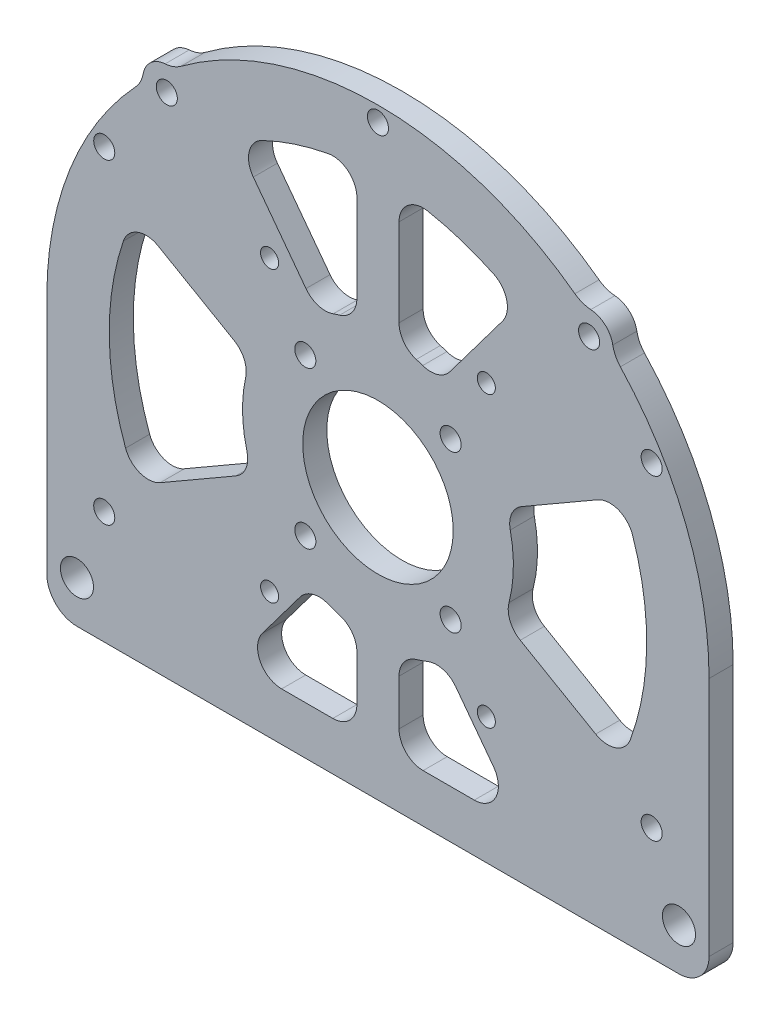
SolidWorks part; units mm, degrees
ref_plane "前视基准面" through (0, 0, 0) normal (0, 0, 1) x (1, 0, 0)
ref_plane "上视基准面" through (0, 0, 0) normal (0, 1, 0) x (1, 0, 0)
ref_plane "右视基准面" through (0, 0, 0) normal (1, 0, 0) x (0, 0, -1)
other "Configuration Table"
sketch "草图2" plane through (0, 0, 0) normal (0, 0, 1) x (1, 0, 0)
  line L0 (40.8909, 11.2177) -> (40.8909, 84.7823) construction
  line L1 (36.7823, 88.8909) -> (-36.7823, 88.8909) construction
  line L2 (-40.8909, 84.7823) -> (-40.8909, 11.2177) construction
  line L3 (40.8909, 11.2177) -> (40.8909, 84.7823)
  line L4 (36.7823, 88.8909) -> (-36.7823, 88.8909)
  line L5 (-40.8909, 84.7823) -> (-40.8909, 11.2177)
  line L6 (-55, 48) -> (-55, 3)
  line L7 (-55, 98) -> (-55, -2) construction
  line L8 (-55, 3) -> (55, 3)
  line L9 (55, 98) -> (55, -2) construction
  line L10 (55, 3) -> (55, 48.115)
  line L11 (-23.2721, 3) -> (23.2721, 3) construction
  circle A0 centre (35.074, 87.25) radius 1.55 construction
  circle A1 centre (-35.074, 87.25) radius 1.55 construction
  circle A2 centre (-50, 10) radius 2.55 construction
  circle A3 centre (50, 10) radius 2.55 construction
  circle A4 centre (-18, 24) radius 1.25 construction
  circle A5 centre (18, 24) radius 1.25 construction
  circle A6 centre (12.07, 35) radius 1.75 construction
  circle A7 centre (-12.07, 35) radius 1.75 construction
  circle A8 centre (-18, 72) radius 1.25 construction
  circle A9 centre (-12.07, 61) radius 1.75 construction
  circle A10 centre (18, 72) radius 1.25 construction
  circle A11 centre (12.07, 61) radius 1.75 construction
  circle A12 centre (35.074, 87.25) radius 1.55
  circle A13 centre (-35.074, 87.25) radius 1.55
  circle A14 centre (-50, 10) radius 2.55
  circle A15 centre (50, 10) radius 2.55
  circle A16 centre (-18, 24) radius 1.25
  circle A17 centre (18, 24) radius 1.25
  circle A18 centre (12.07, 35) radius 1.75
  circle A19 centre (-12.07, 35) radius 1.75
  circle A20 centre (-18, 72) radius 1.25
  circle A21 centre (-12.07, 61) radius 1.75
  circle A22 centre (18, 72) radius 1.25
  circle A23 centre (12.07, 61) radius 1.75
  circle A24 centre (0, 48) radius 12.5 construction
  circle A25 centre (0, 48) radius 12.5
  arc A26 (31.6228, 3) -> (-31.6228, 3) centre (0, 48) ccw
  arc A27 (40.8909, 11.2177) -> (40.8909, 84.7823) centre (0, 48) ccw construction
  circle A28 centre (45.4663, 21.75) radius 1.5
  circle A29 centre (45.4663, 21.75) radius 1.5
  circle A30 centre (45.4663, 74.25) radius 1.5
  circle A31 centre (45.4663, 74.25) radius 1.5
  circle A32 centre (0, 100.5) radius 1.5
  circle A33 centre (0, 100.5) radius 1.5
  circle A34 centre (-45.4663, 21.75) radius 1.5
  circle A35 centre (-45.4663, 21.75) radius 1.5
  circle A36 centre (-45.4663, 74.25) radius 1.5
  circle A37 centre (-45.4663, 74.25) radius 1.5
  arc A38 (36.7823, 88.8909) -> (-36.7823, 88.8909) centre (0, 48) ccw construction
  arc A39 (-40.8909, 84.7823) -> (-40.8909, 11.2177) centre (0, 48) ccw construction
  arc A40 (40.8909, 11.2177) -> (40.8909, 84.7823) centre (0, 48) ccw
  arc A41 (36.7823, 88.8909) -> (-36.7823, 88.8909) centre (0, 48) ccw
  arc A42 (-40.8909, 84.7823) -> (-40.8909, 11.2177) centre (0, 48) ccw
  circle A48 centre (-35.074, 87.25) radius 4
  circle A49 centre (35.074, 87.25) radius 4
  dimension "D1" = 110
  dimension "D8" = 8
  dimension "D9" = 8
  dimension "D7" = 0
  dimension "D2" = 0
  dimension "D3" = 0
  dimension "D4" = 0
  dimension "D5" = 0
  dimension "D6" = 0
extrude "凸台-拉伸1" add sketch "草图2" along normal blind 4
sketch "草图3" plane through (0, 0, 4) normal (0, 0, 1) x (1, 0, 0)
  line L0 (0, 48) -> (-50, 10) construction
  line L1 (50, 10) -> (0, 48) construction
  line L2 (0, 48) -> (35.074, 87.25) construction
  line L3 (-35.074, 87.25) -> (0, 48) construction
  line L4 (0, 48) -> (45.4663, 74.25) construction
  line L5 (0, 100.5) -> (0, 48) construction
  line L6 (0, 48) -> (-45.4663, 74.25) construction
  line L7 (-18, 72) -> (0, 48) construction
  line L8 (0, 48) -> (18, 72) construction
  line L9 (-23.475, 85.9667) -> (-10.085, 68.1133)
  line L10 (0, 92.6379) -> (0, 70.5)
  line L11 (-3.5, 92.5005) -> (-3.5, 70.2261)
  line L12 (-40.502, 66.7651) -> (-21.1752, 55.6067)
  line L13 (-40.0702, 28.3296) -> (-20.8116, 39.4485)
  line L14 (-45.4663, 21.75) -> (0, 48) construction
  line L15 (0, 48) -> (45.4663, 21.75) construction
  line L16 (0, 25.5) -> (0, 3.3621)
  line L17 (-3.5, 25.7739) -> (-3.5, 3.4995)
  line L18 (-24.3222, 10.5704) -> (-10.9795, 28.3607)
  line L19 (-18, 24) -> (0, 48) construction
  line L20 (-24.9709, 11) -> (-3.5, 11)
  line L21 (-55, 3) -> (55, 3) construction
  circle A1 centre (0, 48) radius 22.5
  circle A2 centre (0, 48) radius 44.6379
  circle A3 centre (-35.074, 87.25) radius 1.55 construction
  dimension "D1" = 45
  dimension "D2" = 8
  dimension "D3" = 3.5
  dimension "D4" = 4
  dimension "D5" = 4
  dimension "D6" = 3
  dimension "D7" = 3
  dimension "D8" = 3.5
  dimension "D9" = 8
extrude "切除-拉伸1" cut sketch "草图3" against normal blind 4 contours A1 L18 L20 L17 | L12 A2 L13 A1 | L11 A2 L9 A1
mirror "镜向1" about plane through (0, 0, 0) normal (1, 0, 0) of "切除-拉伸1"
fillet "圆角2" radius 4 4 edges at (-21.1752, 55.6067, 2) (-40.502, 66.7651, 2) (-20.8116, 39.4485, 2) (-40.0702, 28.3296, 2)
fillet "圆角3" radius 4 20 edges at (-3.5, 70.2261, 2) (-23.475, 85.9667, 2) (-3.5, 92.5005, 2) (-10.085, 68.1133, 2) (23.475, 85.9667, 2) (3.5, 70.2261, 2) (3.5, 92.5005, 2) (10.085, 68.1133, 2) (20.8116, 39.4485, 2) (21.1752, 55.6067, 2) (40.502, 66.7651, 2) (40.0702, 28.3296, 2) (24, 11, 2) (3.5, 25.7739, 2) (10.9795, 28.3607, 2) (3.5, 11, 2) (-3.5, 25.7739, 2) (-3.5, 11, 2) (-10.9795, 28.3607, 2) (-24, 11, 2)
fillet "圆角4" radius 5 6 edges at (34.1226, 91.1352, 2) (39.0414, 86.7398, 2) (55, 3, 2) (-55, 3, 2) (-34.1226, 91.1352, 2) (-39.0414, 86.7398, 2)
sketch "草图4" plane through (0, 0, 4) normal (0, 0, 1) x (1, 0, 0)
  circle A0 centre (-45.4663, 74.25) radius 1.75
  circle A1 centre (-35.074, 87.25) radius 1.75
  circle A2 centre (0, 100.5) radius 1.75
  circle A3 centre (35.074, 87.25) radius 1.75
  circle A4 centre (45.4663, 74.25) radius 1.75
  circle A5 centre (18, 72) radius 1.5
  circle A6 centre (-18, 72) radius 1.5
  circle A8 centre (-18, 24) radius 1.5
  circle A9 centre (18, 24) radius 1.5
  circle A10 centre (50, 10) radius 2.75
  circle A11 centre (-50, 10) radius 2.75
  circle A12 centre (45.4663, 21.75) radius 1.75
  circle A13 centre (-45.4663, 21.75) radius 1.75
  dimension "D1" = 3.5
  dimension "D2" = 3.5
  dimension "D3" = 3.5
  dimension "D4" = 3.5
  dimension "D5" = 3.5
  dimension "D6" = 3
  dimension "D7" = 3
  dimension "D8" = 3
  dimension "D9" = 3
  dimension "D10" = 5.5
  dimension "D11" = 5.5
  dimension "D12" = 3.5
  dimension "D13" = 3.5
extrude "切除-拉伸2" cut sketch "草图4" against normal blind 10
